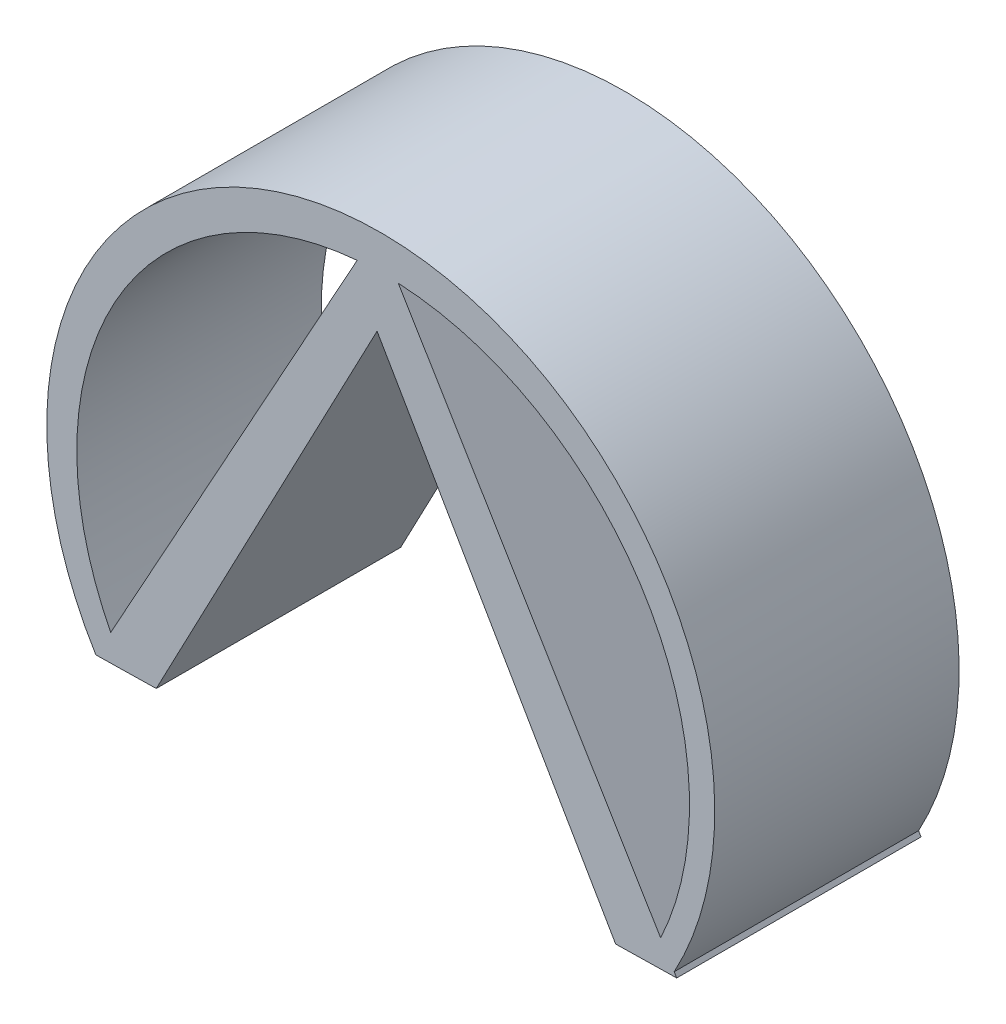
SolidWorks part; units mm, degrees
ref_plane "前视基准面" through (0, 0, 0) normal (0, 0, 1) x (1, 0, 0)
ref_plane "上视基准面" through (0, 0, 0) normal (0, 1, 0) x (1, 0, 0)
ref_plane "右视基准面" through (0, 0, 0) normal (1, 0, 0) x (0, 0, -1)
sketch "草图3" plane through (0, 0, 0) normal (0, 0, 1) x (1, 0, 0)
  line L0 (-46.4305, -35.1662) -> (-1.2538, 50.7344)
  line L1 (60.0473, -33.2206) -> (59.5348, -32.3693)
  line L2 (-1.2538, 68.6127) -> (-1.2683, 68.5865)
  line L3 (-58.7935, -35.3922) -> (-46.4305, -35.1662)
  line L4 (-1.2538, 50.7344) -> (47.5517, -33.4489)
  line L5 (47.5517, -33.4489) -> (60.0473, -33.2206)
  line L6 (56.7594, -27.7588) -> (3.0861, 61.4034)
  line L7 (-1.2381, 68.5868) -> (-1.2538, 68.6127)
  line L8 (-5.3247, 61.2544) -> (-55.742, -29.8765)
  arc A0 (-58.7935, -35.3922) -> (59.5348, -32.3693) centre (-0.5015, 0.2603) cw
  arc A1 (-55.742, -29.8765) -> (-5.3247, 61.2544) centre (-0.0113, -1.1972) cw
  arc A2 (3.0861, 61.4034) -> (56.7594, -27.7588) centre (-0.0113, -1.1972) cw
extrude "凸台-拉伸1" add sketch "草图3" along normal blind 50 contours A0 L3 L0 L4 L5 L1 L8 A1 L6 A2
